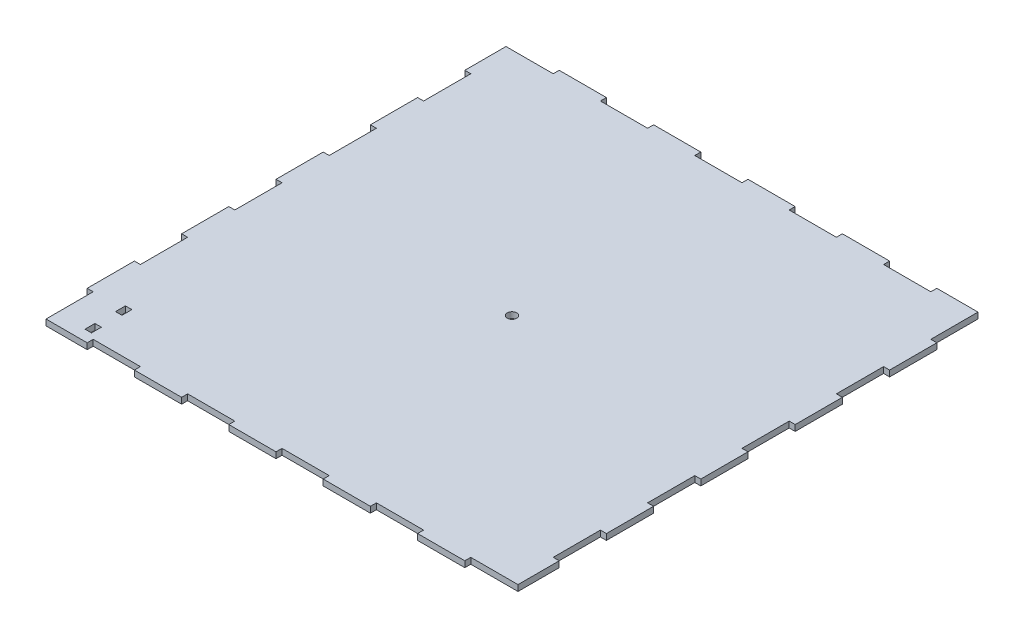
SolidWorks part; units mm, degrees
ref_plane "Front Plane" through (0, 0, 0) normal (0, 0, 1) x (1, 0, 0)
ref_plane "Top Plane" through (0, 0, 0) normal (0, 1, 0) x (1, 0, 0)
ref_plane "Right Plane" through (0, 0, 0) normal (1, 0, 0) x (0, 0, -1)
sketch "Sketch1" plane through (0, 0, 0) normal (0, 1, 0) x (1, 0, 0)
  line L1 (-250, -250) -> (250, -250)
  line L2 (-250, -250) -> (-250, 250)
  line L3 (-250, 250) -> (250, 250)
  line L4 (250, -250) -> (250, 250)
  line L5 (-250, -250) -> (250, 250) construction
  line L6 (-250, 250) -> (250, -250) construction
  point P0 (0, 0)
  dimension "D1" = 500
extrude "Boss-Extrude1" add sketch "Sketch1" along normal mid plane 6.35
sketch "Sketch2" plane through (0, 3.175, 0) normal (0, 1, 0) x (1, 0, 0)
  line L1 (-250, 250) -> (-200, 250)
  line L2 (-250, 250) -> (-250, 243.65)
  line L3 (-250, 243.65) -> (-200, 243.65)
  line L4 (-200, 250) -> (-200, 243.65)
  dimension "D1" = 6.35
  dimension "D2" = 50
extrude "Cut-Extrude1" cut sketch "Sketch2" against normal through all
pattern_linear "LPattern1" count 5 spacing 100 along (1, 0, 0) of "Cut-Extrude1"
sketch "Sketch3" plane through (0, 3.175, 0) normal (0, 1, 0) x (1, 0, 0)
  circle A0 centre (0, 0) radius 5
  dimension "D1" = 10
extrude "Cut-Extrude2" cut sketch "Sketch3" against normal through all
pattern_circular "CirPattern1" count 4 over 360 about axis through (0, 0, 0) along (0, 1, 0) of "LPattern1", "Cut-Extrude1"
sketch "Sketch5" plane through (0, 3.175, 0) normal (0, 1, 0) x (1, 0, 0)
  line L0 (-150, -243.65) -> (-200, -243.65) construction
  line L1 (-213.65, -206.35) -> (-206.8, -206.35)
  line L2 (-213.65, -206.35) -> (-213.65, -195.85)
  line L3 (-213.65, -195.85) -> (-206.8, -195.85)
  line L4 (-206.8, -206.35) -> (-206.8, -195.85)
  line L5 (-213.65, -228.15) -> (-206.8, -228.15)
  line L6 (-213.65, -228.15) -> (-213.65, -238.65)
  line L7 (-213.65, -238.65) -> (-206.8, -238.65)
  line L8 (-206.8, -228.15) -> (-206.8, -238.65)
  line L9 (-243.65, -250) -> (-243.65, -200) construction
  point P8 (-206.8, -201.1)
  point P9 (-206.8, -233.4)
  point P10 (-215.6132, -238.5343)
  dimension "D1" = 6.85
  dimension "D2" = 10.5
  dimension "D3" = 32.3
  dimension "D4" = 5
  dimension "D5" = 30
extrude "Cut-Extrude3" cut sketch "Sketch5" against normal through all
